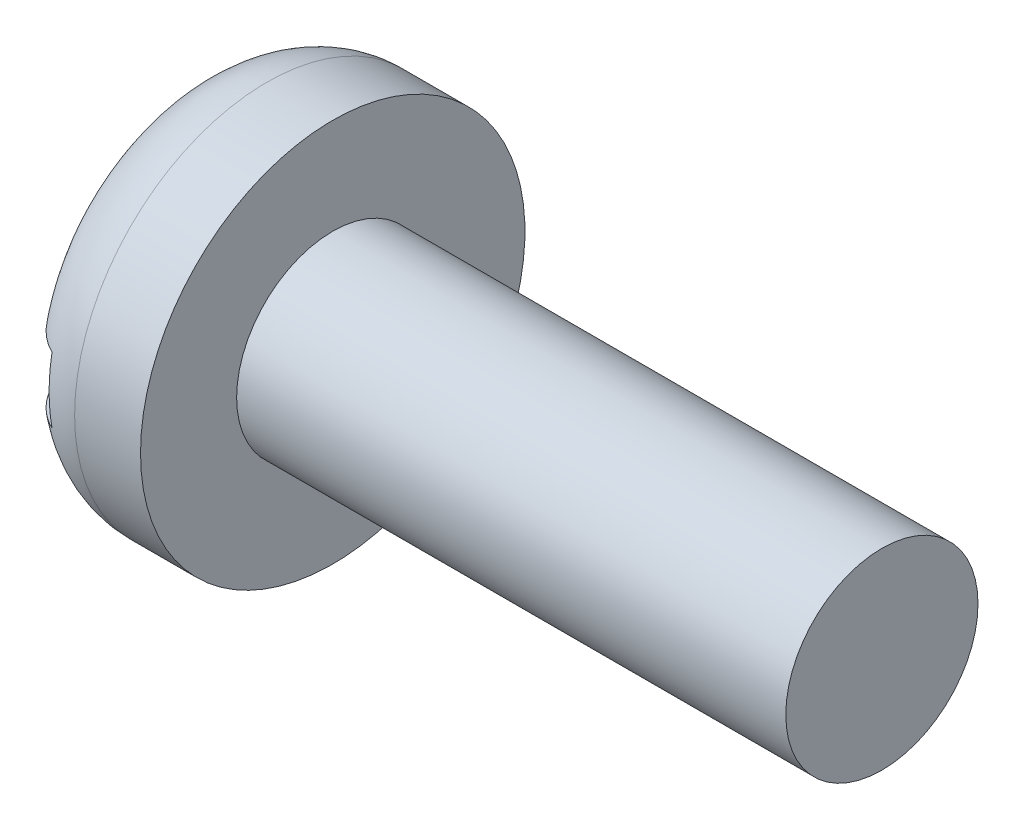
SolidWorks part; units mm, degrees
ref_plane "Plane1" through (0, 0, 0) normal (0, 0, 1) x (1, 0, 0)
ref_plane "Plane2" through (0, 0, 0) normal (0, 1, 0) x (1, 0, 0)
ref_plane "Plane3" through (0, 0, 0) normal (1, 0, 0) x (0, 0, -1)
sketch "BodySke" plane through (0, 0, 0) normal (0, 0, 1) x (1, 0, 0)
  line L0 (2.6, 1.75) -> (2.6, 3.5)
  line L1 (0, 0) -> (0, 2.1)
  line L2 (-25.4, 0) -> (127, 0) construction
  line L3 (12.6, 0) -> (0, 0)
  line L4 (2.6, 1.75) -> (12.6, 1.75)
  line L5 (12.6, 1.75) -> (12.6, 0)
  line L6 (1.4, 3.5) -> (2.6, 3.5)
  line L7 (2.6, -1.75) -> (12.6, -1.75) construction
  line L8 (0, -3.5) -> (2.6, -3.5) construction
  line L9 (3.2, 3.3375) -> (3.2, -6.1875) construction
  line L10 (2.6, 6.35) -> (2.6, -3.175) construction
  arc A0 (0, 2.1) -> (1.4, 3.5) centre (1.4, 2.1) cw
  point P15 (0, 3.5)
  dimension "Head_fillet_rad" = 1.4
  dimension "Head_ht" = 2.6
  dimension "Diameter" = 3.5
  dimension "Length" = 10
  dimension "Head_dia" = 7
  dimension "Advance" = 0.6
  dimension "Thread_nom" = 10
revolve "Base-Revolve" add sketch "BodySke" angle 360 about L2
cosmetic thread "ThreadCosmetic" [suppressed] parameters "Thread_length"=9.4, "Thread_minor"=2.829
sketch "Sketch2" plane through (0, 0, 0) normal (1, 0, 0) x (0, 0, -1)
  line L0 (3.5, -0.6) -> (-3.5, -0.6)
  line L1 (3.5, -0.6) -> (3.5, 0.6)
  line L2 (-3.5, 0.6) -> (3.5, 0.6)
  line L3 (-3.5, 0.6) -> (-3.5, -0.6)
  dimension "D1" = 7
  dimension "D2" = 3.5
  dimension "Slot_width" = 1.2
  dimension "D3" = 0.6
extrude "Slot" cut sketch "Sketch2" along normal blind 0.8
sketch "ThdSchSke" plane through (0, 0, 0) normal (0, 0, 1) x (1, 0, 0)
  line L0 (3.2, -1.4145) -> (2.9651, -1.75)
  line L1 (3.2, -1.4145) -> (3.4349, -1.75)
  line L2 (3.4349, -1.75) -> (3.4349, -2.1875)
  line L3 (-3.175, 0) -> (5.1513, 0) construction
  line L5 (3.4349, -2.1875) -> (2.9651, -2.1875)
  line L6 (2.9651, -2.1875) -> (2.9651, -1.75)
  dimension "Thread_minor" = 2.829
  dimension "Diameter" = 3.5
  dimension "Start" = 3.2
  dimension "SideAngle" = 55
  dimension "VeeAngle" = 70
  dimension "Overcut" = 4.375
revolve "ThreadSchematic" [suppressed] cut sketch "ThdSchSke" angle 360 about L3
pattern_linear "ThdSchPat" [suppressed]
equation "\"D1@Sketch2\" = \"Head_dia@BodySke\""
equation "\"D2@Sketch2\" = \"D1@Sketch2\" / 2"
equation "\"D3@Sketch2\" = \"Slot_width@Sketch2\" / 2"
equation "\"Thread_length@ThreadCosmetic\" = ((sgn( (\"Length@BodySke\" - \"Advance@BodySke\" ) - \"Thread_nom@BodySke\" )-1)*( (\"Length@BodySke\" - \"Advance@BodySke\" ) - \"Thread_nom@BodySke\" ))/-2+ \"Thread_nom@BodySke\""
equation "\"Thread_minor@ThdSchSke\" = \"Thread_minor@ThreadCosmetic\""
equation "\"Diameter@ThdSchSke\" = \"Diameter@BodySke\""
equation "\"Overcut@ThdSchSke\" = \"Diameter@BodySke\" * 1.25"
equation "\"Start@ThdSchSke\" = \"Head_ht@BodySke\" + \"Length@BodySke\" - \"Thread_length@ThreadCosmetic\"  '---Non-countersunk---"
equation "\"Num_threads@ThdSchPat\" = int( \"Thread_length@ThreadCosmetic\" / \"Advance@BodySke\" + 0.999 )  + 1"
equation "\"Advance@ThdSchPat\" = \"Thread_length@ThreadCosmetic\" /  (\"Num_threads@ThdSchPat\" - 1) 'relax it"
